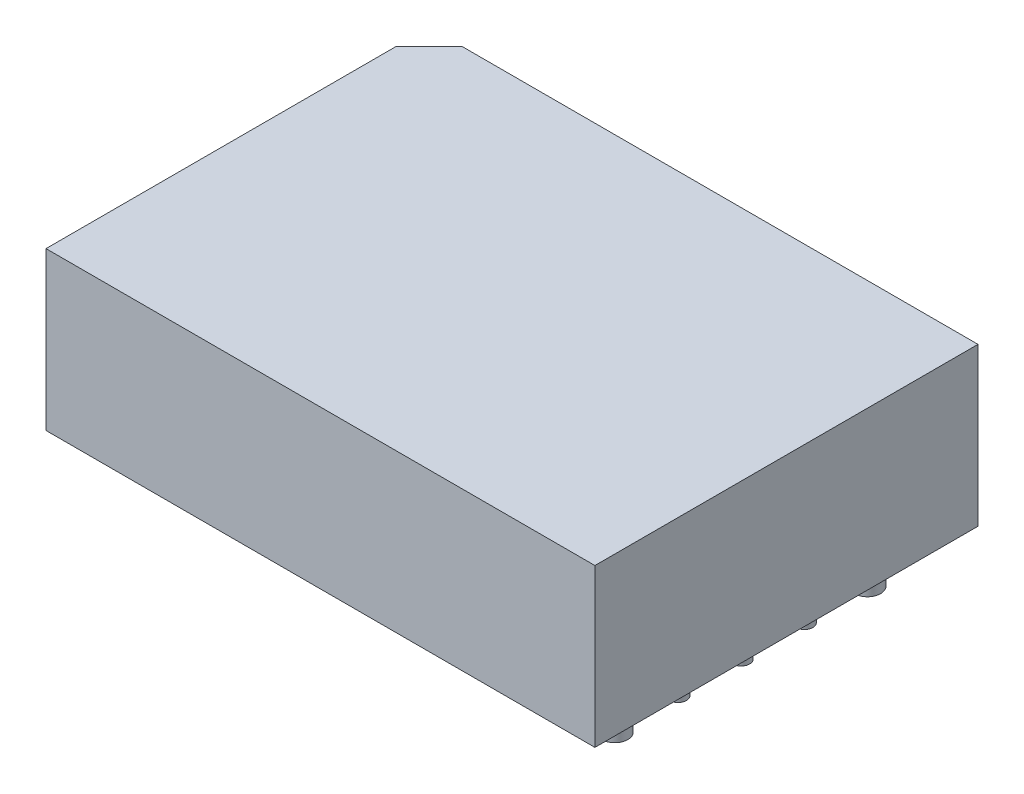
SolidWorks part; units mm, degrees
ref_plane "Front Plane" through (0, 0, 0) normal (0, 0, 1) x (1, 0, 0)
ref_plane "Top Plane" through (0, 0, 0) normal (0, 1, 0) x (1, 0, 0)
ref_plane "Right Plane" through (0, 0, 0) normal (1, 0, 0) x (0, 0, -1)
sketch "Sketch1" plane through (0, 0, 0) normal (0, 1, 0) x (1, 0, 0)
  line L0 (-31.1, 23.1) -> (-33.1, 21.1)
  line L1 (0, 0) -> (-33.1, 0)
  line L2 (0, 0) -> (0, 23.1)
  line L3 (0, 23.1) -> (-31.1, 23.1)
  line L4 (-33.1, 0) -> (-33.1, 21.1)
  point P1 (-33.1, 23.1)
  dimension "D1" = 33.1
  dimension "D2" = 23.1
extrude "Boss-Extrude1" add sketch "Sketch1" along normal blind 9.5
sketch "Sketch4" plane through (0, 9.5, 0) normal (0, 1, 0) x (1, 0, 0)
  line L0 (-33.1, 0) -> (0, 0) construction
  line L1 (0, 0) -> (0, 23.1) construction
  circle A0 centre (-30.64, 19.14) radius 0.51
  circle A1 centre (-30.64, 5.0042) radius 0.51
  circle A2 centre (-2.7, 19.14) radius 0.51
  circle A3 centre (-2.7, 15.33) radius 0.51
  circle A4 centre (-2.7, 11.52) radius 0.51
  circle A5 centre (-2.7, 7.71) radius 0.51
  circle A6 centre (-2.7, 3.9) radius 0.51
  circle A7 centre (-2.7, 3.9) radius 0.785
  circle A8 centre (-2.7, 19.14) radius 0.785
  circle A9 centre (-30.64, 11.52) radius 0.51
  dimension "D2" = 1.02
  dimension "D3" = 1.57
  dimension "D1" = 27.94
  dimension "D4" = 3.9
  dimension "D5" = 3.81
  dimension "D6" = 7.62
  dimension "D7" = 11.43
  dimension "D8" = 15.24
  dimension "D9" = 2.7
extrude "Boss-Extrude2" add sketch "Sketch4" against normal blind 12 contours A2 | A8 A2 | A3 | A6 | A7 A6 | A5 | A4 | A1 | A0 | A9
